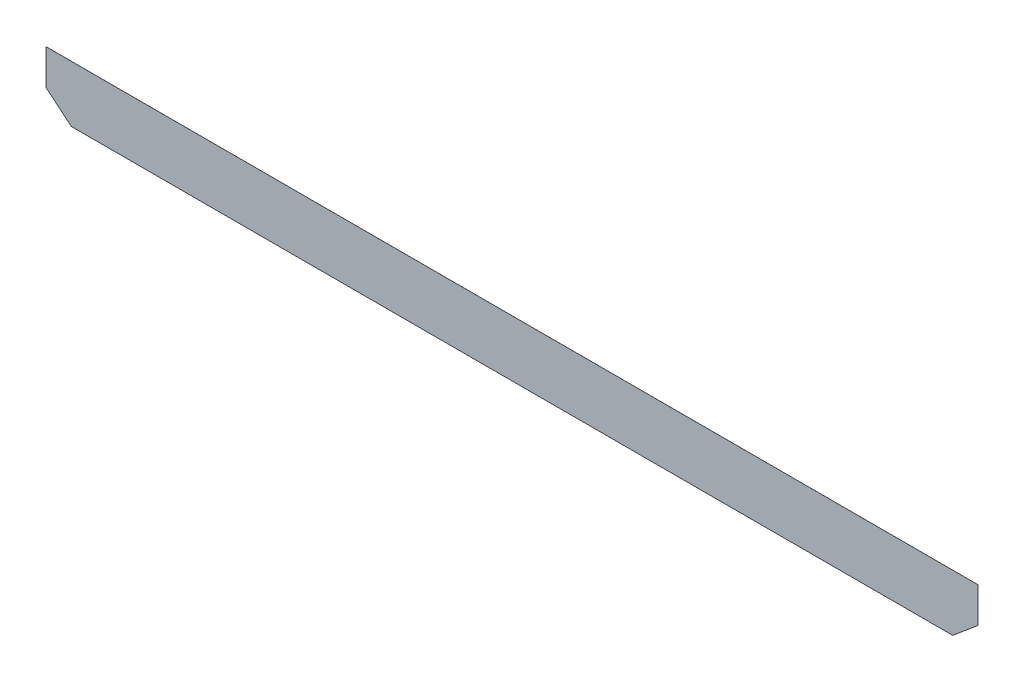
SolidWorks part; units mm, degrees
ref_plane "Front Plane" through (0, 0, 0) normal (0, 0, 1) x (1, 0, 0)
ref_plane "Top Plane" through (0, 0, 0) normal (0, 1, 0) x (1, 0, 0)
ref_plane "Right Plane" through (0, 0, 0) normal (1, 0, 0) x (0, 0, -1)
sketch "Sketch1" plane through (0, 0, 0) normal (0, 0, 1) x (1, 0, 0)
  line L1 (0, 0) -> (33, 0)
  line L2 (0, 0) -> (0, 2)
  line L3 (0, 2) -> (33, 2)
  line L4 (33, 0) -> (33, 2)
  dimension "D1" = 33
  dimension "D2" = 2
extrude "Boss-Extrude1" add sketch "Sketch1" along normal blind 0.001
sketch "Sketch2" plane through (0, 0, 0) normal (0, 0, -1) x (-1, 0, 0)
  line L0 (0, 0.75) -> (-0.8938, 0)
  line L1 (0, 2) -> (0, 0) construction
  line L2 (0, 0) -> (-33, 0) construction
  line L3 (-16.5, 2) -> (-16.5, 0) construction
  line L4 (-33, 2) -> (0, 2) construction
  line L5 (-33, 0.75) -> (-32.1062, 0)
  line L6 (0, 0.75) -> (0, 0)
  line L7 (0, 0) -> (-0.8938, 0)
  line L8 (-33, 0) -> (-32.1062, 0)
  line L9 (-33, 0.75) -> (-33, 0)
  line L10 (-33, 0.75) -> (-32.1062, 0)
  line M5 (-33, 2) -> (-33, 0)
  line M6 (-33, 0) -> (0, 0)
  dimension "D1" = 40
  dimension "D2" = 0.75
extrude "Cut-Extrude1" cut sketch "Sketch2" against normal blind 1 contours L5 M5 M6 | L7 L0 L6
